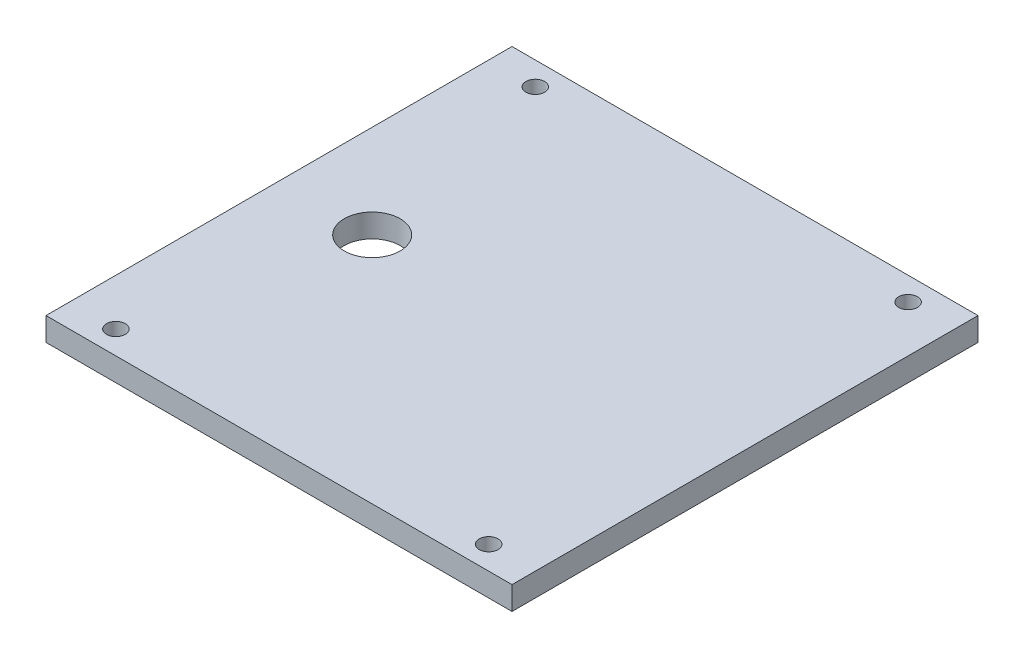
SolidWorks part; units mm, degrees
material "6061 Alloy"
ref_plane "Front" through (0, 0, 0) normal (0, 0, 1) x (1, 0, 0)
ref_plane "Top" through (0, 0, 0) normal (0, 1, 0) x (1, 0, 0)
ref_plane "Right" through (0, 0, 0) normal (1, 0, 0) x (0, 0, -1)
sketch "Sketch2" plane through (0, 0, 0) normal (0, 1, 0) x (1, 0, 0)
  line L0 (-55, 0) -> (55, 0) construction
  line L1 (-65.3715, -63.5) -> (61.6285, -63.5)
  line L2 (-65.3715, -63.5) -> (-65.3715, 63.5)
  line L3 (-65.3715, 63.5) -> (61.6285, 63.5)
  line L4 (61.6285, -63.5) -> (61.6285, 63.5)
  line L5 (-65.3715, -63.5) -> (61.6285, 63.5) construction
  line L6 (-65.3715, 63.5) -> (61.6285, -63.5) construction
  point P0 (-1.8715, 0)
  dimension "D1" = 127
  dimension "D2" = 127
extrude "Boss-Extrude1" add sketch "Sketch2" along normal blind 6.35
sketch "Sketch6" plane through (0, 6.35, 0) normal (0, 1, 0) x (1, 0, 0)
  line L0 (-1.8715, 63.5) -> (-1.8715, -63.5) construction
  line L1 (61.6285, 63.5) -> (-65.3715, 63.5) construction
  line L2 (-65.3715, -63.5) -> (61.6285, -63.5) construction
  line L3 (-65.3715, 63.5) -> (-65.3715, -63.5) construction
  line L4 (-65.3715, 0) -> (61.6285, 0) construction
  line L5 (61.6285, -63.5) -> (61.6285, 63.5) construction
  circle A0 centre (-52.6715, 57.15) radius 2.5527
  circle A2 centre (-52.6715, -57.15) radius 2.5527
  circle A3 centre (48.9285, -57.15) radius 2.5527
  circle A4 centre (48.9285, 57.15) radius 2.5527
  dimension "D1" = 5.1054
  dimension "D3" = 12.7
  dimension "D2" = 6.35
extrude "Cut-Extrude3" cut sketch "Sketch6" against normal blind 9.525
sketch "Sketch7" plane through (0, 6.35, 0) normal (0, 1, 0) x (1, 0, 0)
  line L1 (61.6285, 63.5) -> (-65.3715, 63.5) construction
  line L2 (-65.3715, -63.5) -> (61.6285, -63.5) construction
  line L3 (-39.9715, 63.5) -> (-39.9715, -63.5) construction
  line L4 (-65.3715, 63.5) -> (-65.3715, -63.5) construction
  circle A1 centre (-39.9715, 0) radius 7.62
  dimension "D3" = 15.24
  dimension "D2" = 25.4
extrude "Cut-Extrude4" cut sketch "Sketch7" against normal up to next
